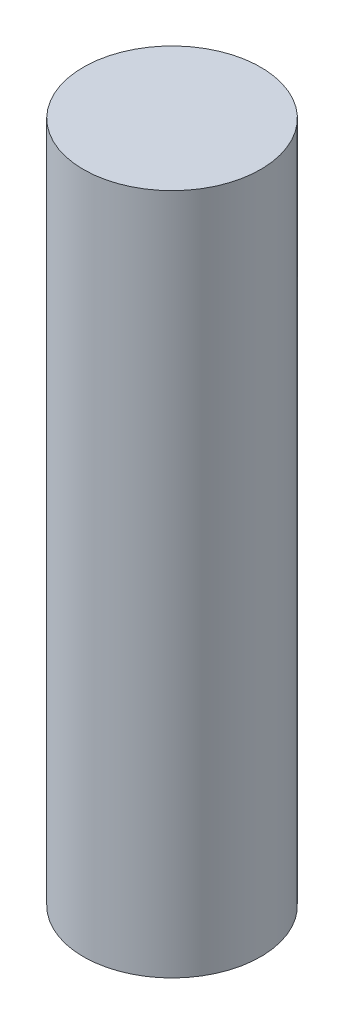
SolidWorks part; units mm, degrees
ref_plane "Front Plane" through (0, 0, 0) normal (0, 0, 1) x (1, 0, 0)
ref_plane "Top Plane" through (0, 0, 0) normal (0, 1, 0) x (1, 0, 0)
ref_plane "Right Plane" through (0, 0, 0) normal (1, 0, 0) x (0, 0, -1)
sketch "Sketch1" plane through (0, 0, 0) normal (0, 1, 0) x (1, 0, 0)
  circle A0 centre (0, 0) radius 13
  dimension "D1" = 26
extrude "Boss-Extrude1" add sketch "Sketch1" along normal blind 100
sketch "Sketch2" plane through (0, 0, 0) normal (0, -1, 0) x (1, 0, 0)
  circle A0 centre (0, 0) radius 10
  circle A1 centre (0, 22) radius 5
  circle A2 centre (0, -22) radius 5
  dimension "D2" = 10
  dimension "D3" = 20
  dimension "D4" = 10
  dimension "D1" = 22
  dimension "D5" = 22
extrude "Cut-Extrude1" cut sketch "Sketch2" against normal blind 20
